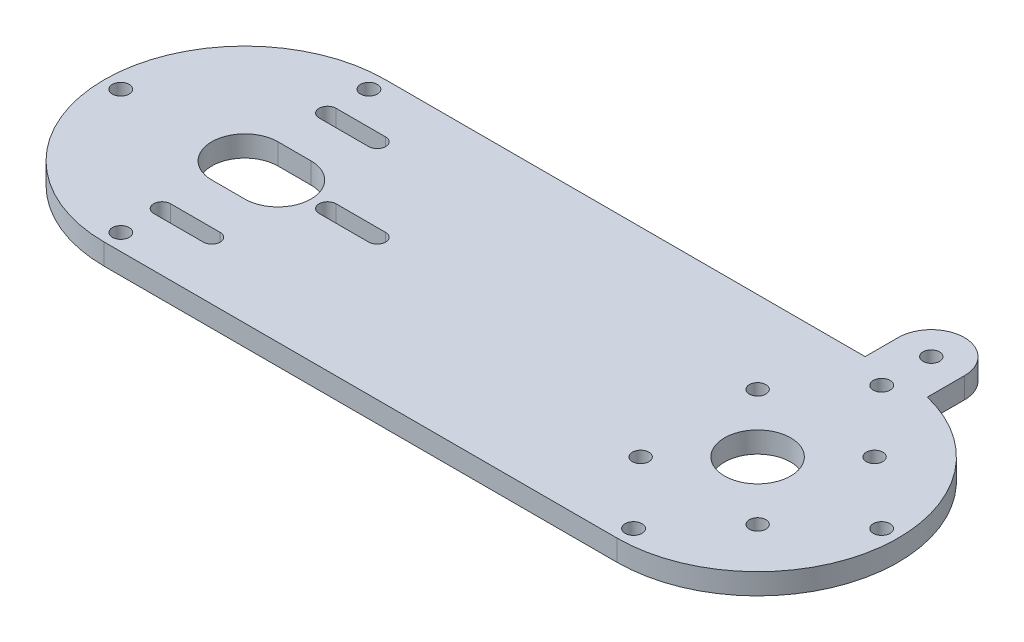
SolidWorks part; units mm, degrees
ref_plane "Front Plane" through (0, 0, 0) normal (0, 0, 1) x (1, 0, 0)
ref_plane "Top Plane" through (0, 0, 0) normal (0, 1, 0) x (1, 0, 0)
ref_plane "Right Plane" through (0, 0, 0) normal (1, 0, 0) x (0, 0, -1)
sketch "Sketch1" plane through (0, 0, 0) normal (0, 1, 0) x (1, 0, 0)
  line L0 (-155, 0) -> (0, 0) construction
  line L1 (-155, 42.5) -> (0, 42.5)
  line L6 (-155, -42.5) -> (0, -42.5)
  line L7 (-155, 0) -> (-145, 0) construction
  line L10 (-155, 10) -> (-145, 10)
  line L13 (-155, -10) -> (-145, -10)
  line L16 (-155, 25) -> (-140, 25) construction
  line L19 (17.6777, -17.6777) -> (-17.6777, 17.6777) construction
  line L20 (-155, 27.55) -> (-140, 27.55)
  line L21 (-17.6777, -17.6777) -> (17.6777, 17.6777) construction
  line L24 (-155, 22.45) -> (-140, 22.45)
  line L25 (-10, 41.3068) -> (-10, 52.5)
  line L26 (0, 0) -> (0, 29.185) construction
  line L27 (0, 29.185) -> (0, 52.5) construction
  line L28 (10, 52.5) -> (10, 41.3068)
  line L29 (-155, -25) -> (-140, -25) construction
  line L30 (-155, -22.45) -> (-140, -22.45)
  line L31 (-155, -27.55) -> (-140, -27.55)
  line L32 (-130, 0) -> (-115, 0) construction
  line L33 (-130, 2.55) -> (-115, 2.55)
  line L34 (-130, -2.55) -> (-115, -2.55)
  line L35 (-135, 76.729) -> (-135, -79.5693) construction
  circle A1 centre (-155, 0) radius 10 construction
  circle A4 centre (-155, 0) radius 14.2875 construction
  circle A5 centre (0, 0) radius 10
  circle A8 centre (-155, 0) radius 37.5 construction
  circle A13 centre (-155, 0) radius 42.5
  circle A14 centre (0, 0) radius 42.5
  circle A15 centre (0, 0) radius 37.5 construction
  circle A16 centre (0, 37.5) radius 2.55
  circle A17 centre (37.5, 0) radius 2.55
  circle A18 centre (0, -37.5) radius 2.55
  circle A19 centre (-37.5, 0) radius 2.55 construction
  circle A29 centre (0, 0) radius 25 construction
  circle A30 centre (-17.6777, 17.6777) radius 2.5
  circle A31 centre (17.6777, -17.6777) radius 2.5
  circle A32 centre (-17.6777, -17.6777) radius 2.5
  circle A33 centre (17.6777, 17.6777) radius 2.5
  circle A36 centre (0, 52.5) radius 2.5
  circle A37 centre (0, 52.5) radius 10
  circle A38 centre (-192.5, 0) radius 2.55
  circle A39 centre (-155, 37.5) radius 2.55
  circle A40 centre (-155, -37.5) radius 2.55
  circle A41 centre (-117.5, 0) radius 2.55 construction
  arc A42 (-155, 10) -> (-155, -10) centre (-155, 0) ccw
  arc A43 (-145, -10) -> (-145, 10) centre (-145, 0) ccw
  circle A44 centre (-155, 0) radius 25 construction
  arc A45 (-155, 27.55) -> (-155, 22.45) centre (-155, 25) ccw
  arc A46 (-140, 22.45) -> (-140, 27.55) centre (-140, 25) ccw
  arc A47 (-155, -22.45) -> (-155, -27.55) centre (-155, -25) ccw
  arc A48 (-140, -27.55) -> (-140, -22.45) centre (-140, -25) ccw
  arc A49 (-130, 2.55) -> (-130, -2.55) centre (-130, 0) ccw
  arc A50 (-115, -2.55) -> (-115, 2.55) centre (-115, 0) ccw
  point P31 (-150, 0)
  point P41 (-147.5, 25)
  point P46 (-147.5, -25)
  point P62 (-122.5, 0)
  dimension "D2" = 20
  dimension "D4" = 5.1
  dimension "D5" = 45
  dimension "D6" = 28.575
  dimension "D7" = 20
  dimension "D10" = 85
  dimension "D8" = 75
  dimension "D11" = 5.1
  dimension "D12" = 75
  dimension "D13" = 50
  dimension "D14" = 50
  dimension "D15" = 5
  dimension "D16" = 15
  dimension "D18" = 5
  dimension "D19" = 20
  dimension "D20" = 10
  dimension "D3" = 155
  dimension "D17" = 5.1
  dimension "D21" = 20
extrude "Boss-Extrude1" add sketch "Sketch1" against normal blind 6.35
